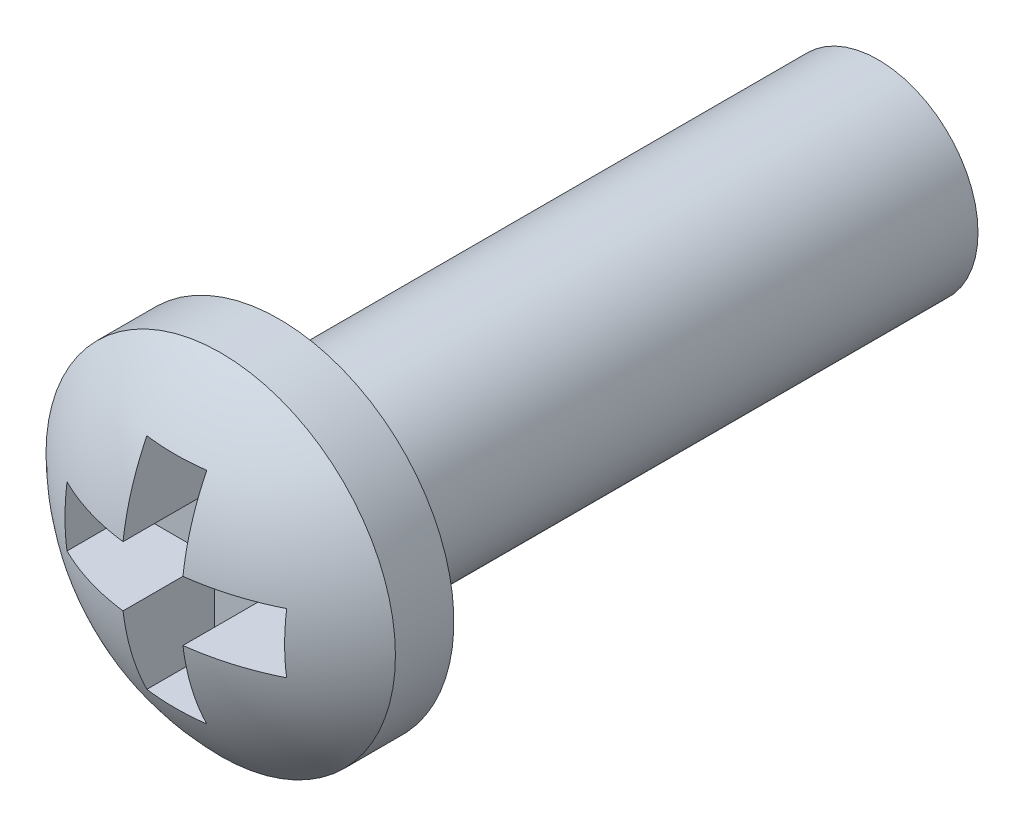
SolidWorks part; units mm, degrees
ref_plane "前视基准面" through (0, 0, 0) normal (0, 0, 1) x (1, 0, 0)
ref_plane "上视基准面" through (0, 0, 0) normal (0, 1, 0) x (1, 0, 0)
ref_plane "右视基准面" through (0, 0, 0) normal (1, 0, 0) x (0, 0, -1)
other "Configuration Table"
sketch "草图1" plane through (0, 0, 0) normal (0, 0, 1) x (1, 0, 0)
  circle A0 centre (0, 0) radius 1
extrude "标准杆径_头下长度" add sketch "草图1" against normal blind 6
sketch "草图2" plane through (0, 0, 0) normal (0, 0, 1) x (1, 0, 0)
  circle A0 centre (0, 0) radius 1.9
sketch "草图4" plane through (0, 0, 0) normal (0, 1, 0) x (1, 0, 0)
  line L0 (0, 0) -> (2.25, 0)
  line L1 (2.25, 0) -> (2.25, -0.1843)
  line L2 (0, -1.2) -> (0, 0)
  line L3 (0, 2) -> (0, -3.2) construction
  arc A0 (2.25, -0.1843) -> (0, -1.2) centre (0, 1.8) cw
sketch "草图5" plane through (0, 0, 0) normal (0, 0, 1) x (1, 0, 0)
  line L0 (-0.3, -1.1) -> (0.3, -1.1)
  line L1 (0.3, -1.1) -> (0.3, -0.3)
  line L2 (0.3, -0.3) -> (1.1, -0.3)
  line L3 (1.1, -0.3) -> (1.1, 0.3)
  line L4 (1.1, 0.3) -> (0.3, 0.3)
  line L5 (0.3, 0.3) -> (0.3, 1.1)
  line L6 (0.3, 1.1) -> (-0.3, 1.1)
  line L7 (-0.3, 1.1) -> (-0.3, 0.3)
  line L8 (-0.3, 0.3) -> (-1.1, 0.3)
  line L9 (-1.1, 0.3) -> (-1.1, -0.3)
  line L10 (-1.1, -0.3) -> (-0.3, -0.3)
  line L11 (-0.3, -0.3) -> (-0.3, -1.1)
sketch "草图6" plane through (0, 0, 0) normal (0, 1, 0) x (1, 0, 0)
  line L0 (0, 0) -> (1.75, 0)
  line L1 (1.75, 0) -> (1.75, -0.5854)
  line L2 (0, -1.3) -> (0, 0)
  line L3 (0, 2) -> (0, -3.3) construction
  arc A0 (1.75, -0.5854) -> (0, -1.3) centre (0, 1.2) cw
revolve "已确认_十字槽盘头" add sketch "草图6" angle 360 about L3
sketch "草图7" plane through (0, 0, 0) normal (0, 0, 1) x (1, 0, 0)
  line L0 (-0.3, -1.1) -> (0.3, -1.1)
  line L1 (0.3, -1.1) -> (0.3, -0.3)
  line L2 (0.3, -0.3) -> (1.1, -0.3)
  line L3 (1.1, -0.3) -> (1.1, 0.3)
  line L4 (1.1, 0.3) -> (0.3, 0.3)
  line L5 (0.3, 0.3) -> (0.3, 1.1)
  line L6 (0.3, 1.1) -> (-0.3, 1.1)
  line L7 (-0.3, 1.1) -> (-0.3, 0.3)
  line L8 (-0.3, 0.3) -> (-1.1, 0.3)
  line L9 (-1.1, 0.3) -> (-1.1, -0.3)
  line L10 (-1.1, -0.3) -> (-0.3, -0.3)
  line L11 (-0.3, -0.3) -> (-0.3, -1.1)
extrude "十字槽_PH1_简化" cut sketch "草图7" against normal blind 0.96 from offset 1.31
